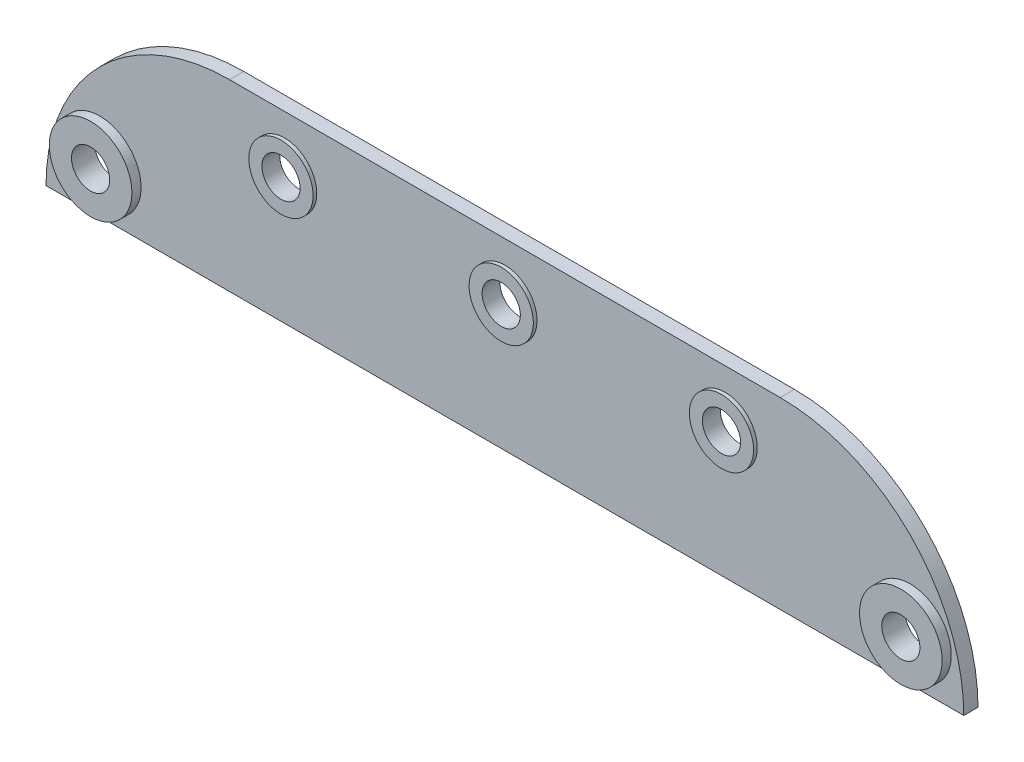
SolidWorks part; units mm, degrees
ref_plane "Front Plane" through (0, 0, 0) normal (0, 0, 1) x (1, 0, 0)
ref_plane "Top Plane" through (0, 0, 0) normal (0, 1, 0) x (1, 0, 0)
ref_plane "Right Plane" through (0, 0, 0) normal (1, 0, 0) x (0, 0, -1)
sketch "Sketch1" plane through (0, 0, 0) normal (0, 0, 1) x (1, 0, 0)
  line L0 (-48, 8) -> (0, 8) construction
  line L1 (-60, 20) -> (60, 20)
  line L3 (-100, -20) -> (100, -20)
  line L5 (-100, 20) -> (100, -20) construction
  line L6 (-100, -20) -> (100, 20) construction
  line L7 (0, 8) -> (48, 8) construction
  line L8 (0, 37.7846) -> (0, -45.3301) construction
  line L9 (-110.8398, 0) -> (122.7505, 0) construction
  circle A0 centre (0, 8) radius 4.165
  circle A1 centre (48, 8) radius 4.165
  circle A2 centre (-48, 8) radius 4.165
  circle A3 centre (-88.2843, -10) radius 4.165
  circle A4 centre (88.2843, -10) radius 4.165
  circle A5 centre (-48, 8) radius 19 construction
  arc A7 (-60, 20) -> (-100, -20) centre (-60, -20) ccw
  arc A8 (60, 20) -> (100, -20) centre (60, -20) cw
  circle A9 centre (-88.2843, -10) radius 10 construction
  circle A10 centre (88.2843, -10) radius 10 construction
  point P0 (0, 0)
  point P25 (0, 20)
  point P26 (0, -20)
  dimension "D4" = 8.33
  dimension "D6" = 38
  dimension "D1" = 40
  dimension "D2" = 200
  dimension "D3" = 12
  dimension "D5" = 48
  dimension "D7" = 40
  dimension "D8" = 200
extrude "Boss-Extrude1" add sketch "Sketch1" along normal blind 3.1
sketch "Sketch2" plane through (0, 0, 3.1) normal (0, 0, 1) x (1, 0, 0)
  circle A1 centre (48, 8) radius 4.165 construction
  circle A2 centre (0, 8) radius 4.165 construction
  circle A3 centre (-48, 8) radius 4.165 construction
  circle A6 centre (48, 8) radius 4.165
  circle A7 centre (0, 8) radius 4.165
  circle A8 centre (-48, 8) radius 4.165
  circle A11 centre (-48, 8) radius 7
  circle A12 centre (0, 8) radius 7
  circle A13 centre (48, 8) radius 7
  dimension "D1" = 14
extrude "Boss-Extrude3" add sketch "Sketch2" along normal blind 0.8
sketch "Sketch4" plane through (0, 0, 3.1) normal (0, 0, 1) x (1, 0, 0)
  circle A0 centre (88.2843, -10) radius 4.165 construction
  circle A1 centre (-88.2843, -10) radius 4.165 construction
  circle A2 centre (88.2843, -10) radius 4.165
  circle A3 centre (-88.2843, -10) radius 4.165
  circle A4 centre (-88.2843, -10) radius 9
  circle A5 centre (88.2843, -10) radius 9
  dimension "D1" = 18
extrude "Boss-Extrude4" add sketch "Sketch4" along normal blind 2
